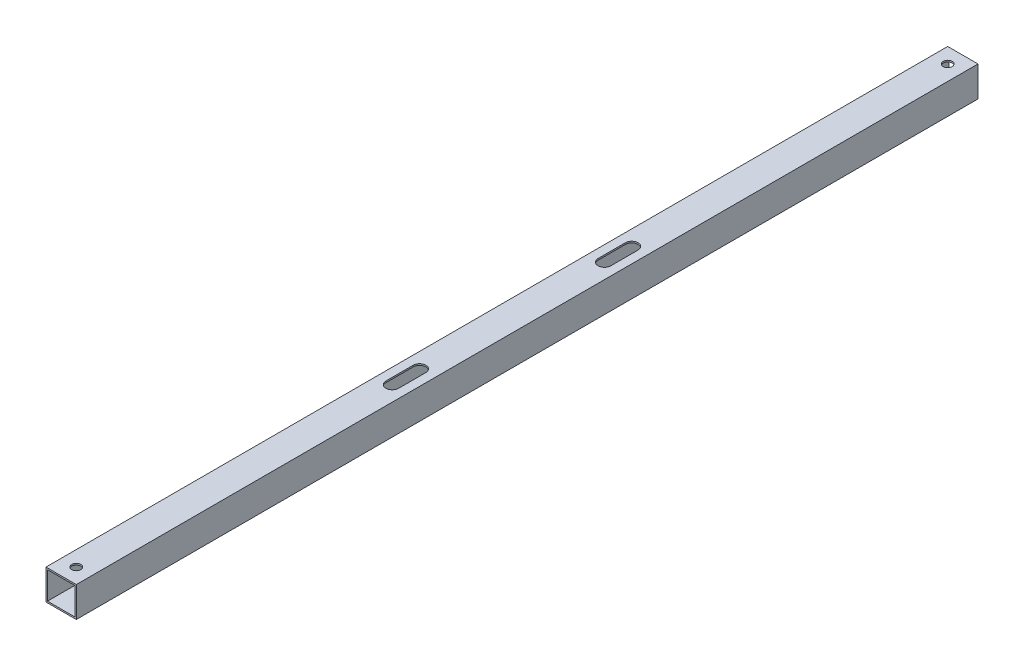
SolidWorks part; units mm, degrees
material "6063-T5"
ref_plane "前视基准面" through (0, 0, 0) normal (0, 0, 1) x (1, 0, 0)
ref_plane "上视基准面" through (0, 0, 0) normal (0, 1, 0) x (1, 0, 0)
ref_plane "右视基准面" through (0, 0, 0) normal (1, 0, 0) x (0, 0, -1)
sketch "草图1" plane through (0, 0, 0) normal (0, 0, 1) x (1, 0, 0)
  line L0 (-9, -9) -> (-9, 9)
  line L1 (-10, -10) -> (10, -10)
  line L2 (-10, -10) -> (-10, 10)
  line L3 (-10, 10) -> (10, 10)
  line L4 (10, -10) -> (10, 10)
  line L5 (0, 10) -> (0, -10) construction
  line L6 (-10, 0) -> (10, 0) construction
  line L7 (-9, 9) -> (9, 9)
  line L8 (9, -9) -> (9, 9)
  line L9 (-9, -9) -> (9, -9)
  point P0 (0, 0)
  dimension "D1" = 20
  dimension "D2" = 1
extrude "凸台-拉伸1" add sketch "草图1" along normal mid plane 595
sketch "草图2" plane through (0, 10, 0) normal (0, 1, 0) x (1, 0, 0)
  line L0 (0, -297.5) -> (0, -287.5) construction
  line L1 (10, -297.5) -> (-10, -297.5) construction
  circle A0 centre (0, -287.5) radius 3
  dimension "D1" = 6
  dimension "D2" = 10
extrude "切除-拉伸1" cut sketch "草图2" against normal blind 10
mirror "镜向1" about plane through (0, 0, 0) normal (0, 0, 1) of "切除-拉伸1"
sketch "草图3" [suppressed] plane through (0, 9, 0) normal (0, -1, 0) x (1, 0, 0)
  line L0 (0, -90) -> (0, -80) construction
  line L1 (-10, -90) -> (10, -90) construction
  circle A0 centre (0, -80) radius 3
  dimension "D1" = 6
  dimension "D2" = 10
extrude "切除-拉伸2" [suppressed] cut sketch "草图3" against normal blind 10
sketch "草图4" plane through (0, -9, 0) normal (0, 1, 0) x (1, 0, 0)
  circle A0 centre (0, -79) radius 2 construction
  circle A1 centre (0, -61) radius 2 construction
  circle A2 centre (0, -79) radius 2
  circle A3 centre (0, -61) radius 2
extrude "切除-拉伸3" cut sketch "草图4" against normal blind 10
sketch "草图5" plane through (0, 9, 0) normal (0, -1, 0) x (1, 0, 0)
  line L0 (0, 79) -> (0, 61) construction
  line L1 (4.2, 79) -> (4.2, 61)
  line L2 (-4.2, 79) -> (-4.2, 61)
  arc A0 (4.2, 79) -> (-4.2, 79) centre (0, 79) ccw
  arc A1 (-4.2, 61) -> (4.2, 61) centre (0, 61) ccw
  point P4 (0, 70)
  dimension "D1" = 4.2
extrude "切除-拉伸4" cut sketch "草图5" against normal blind 10
mirror "镜向2" about plane through (0, 0, 0) normal (0, 0, 1) of "切除-拉伸3", "切除-拉伸4"
